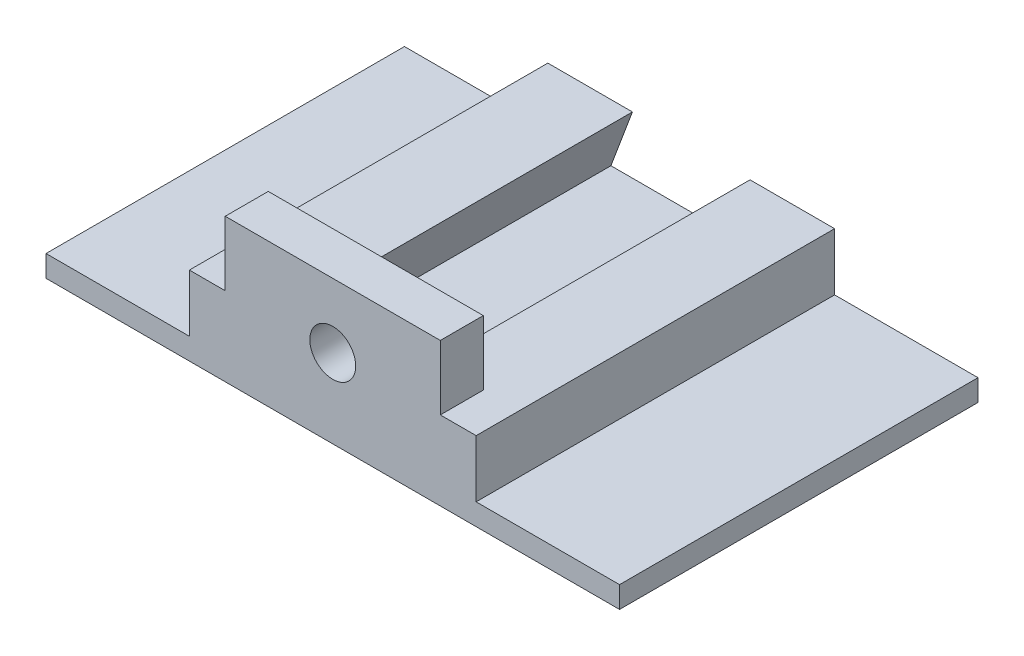
SolidWorks part; units mm, degrees
ref_plane "Alzado" through (0, 0, 0) normal (0, 0, 1) x (1, 0, 0)
ref_plane "Planta" through (0, 0, 0) normal (0, 1, 0) x (1, 0, 0)
ref_plane "Vista lateral" through (0, 0, 0) normal (1, 0, 0) x (0, 0, -1)
sketch "Croquis1" plane through (0, 0, 0) normal (0, 0, 1) x (1, 0, 0)
  line L0 (15.9, 5.5) -> (14.4, 1.5)
  line L1 (0, 0) -> (40, 0)
  line L2 (0, 0) -> (0, 5.5)
  line L3 (0, 5.5) -> (15.9, 5.5)
  line L4 (40, 0) -> (40, 5.5)
  line L5 (14.4, 1.5) -> (25.6, 1.5)
  line L6 (25.6, 1.5) -> (24.1, 5.5)
  line L7 (20, 1.5) -> (20, 5.5) construction
  line L8 (24.1, 5.5) -> (40, 5.5)
  line L9 (15.9, 5.5) -> (20, 5.5) construction
  line L10 (20, 5.5) -> (24.1, 5.5) construction
  line L11 (20, 1.5) -> (20, 0) construction
  dimension "D1" = 40
  dimension "D2" = 5.5
  dimension "D3" = 11.2
  dimension "D4" = 8.2
  dimension "D5" = 4
extrude "Saliente-Extruir1" add sketch "Croquis1" along normal blind 25
sketch "Croquis2" plane through (0, 0, 25) normal (0, 0, 1) x (1, 0, 0)
  line L0 (0, 0) -> (40, 0) construction
  line L1 (12.5, 0) -> (27.5, 0)
  line L2 (12.5, 0) -> (12.5, 10)
  line L3 (12.5, 10) -> (27.5, 10)
  line L4 (27.5, 0) -> (27.5, 10)
  line L5 (20, 0) -> (20, 10) construction
  line L6 (25.6, 1.5) -> (14.4, 1.5) construction
  circle A0 centre (20, 5.5) radius 1.6
  dimension "D3" = 3.2
  dimension "D1" = 15
  dimension "D2" = 10
  dimension "D4" = 4
extrude "Saliente-Extruir2" add sketch "Croquis2" against normal blind 3
sketch "Croquis3" plane through (0, 0, 25) normal (0, 0, 1) x (1, 0, 0)
  line L0 (20, 0) -> (20, 10) construction
  line L1 (0, 5.5) -> (10, 5.5)
  line L2 (0, 5.5) -> (0, 1.5)
  line L3 (0, 1.5) -> (10, 1.5)
  line L4 (10, 5.5) -> (10, 1.5)
  line L5 (0, 0) -> (40, 0) construction
  line L6 (27.5, 10) -> (12.5, 10) construction
  line L7 (14.4, 1.5) -> (25.6, 1.5) construction
  line L8 (40, 1.5) -> (30, 1.5)
  line L9 (30, 5.5) -> (30, 1.5)
  line L10 (40, 5.5) -> (30, 5.5)
  line L11 (40, 5.5) -> (40, 1.5)
  dimension "D1" = 10
extrude "Cortar-Extruir1" cut sketch "Croquis3" against normal blind 33
